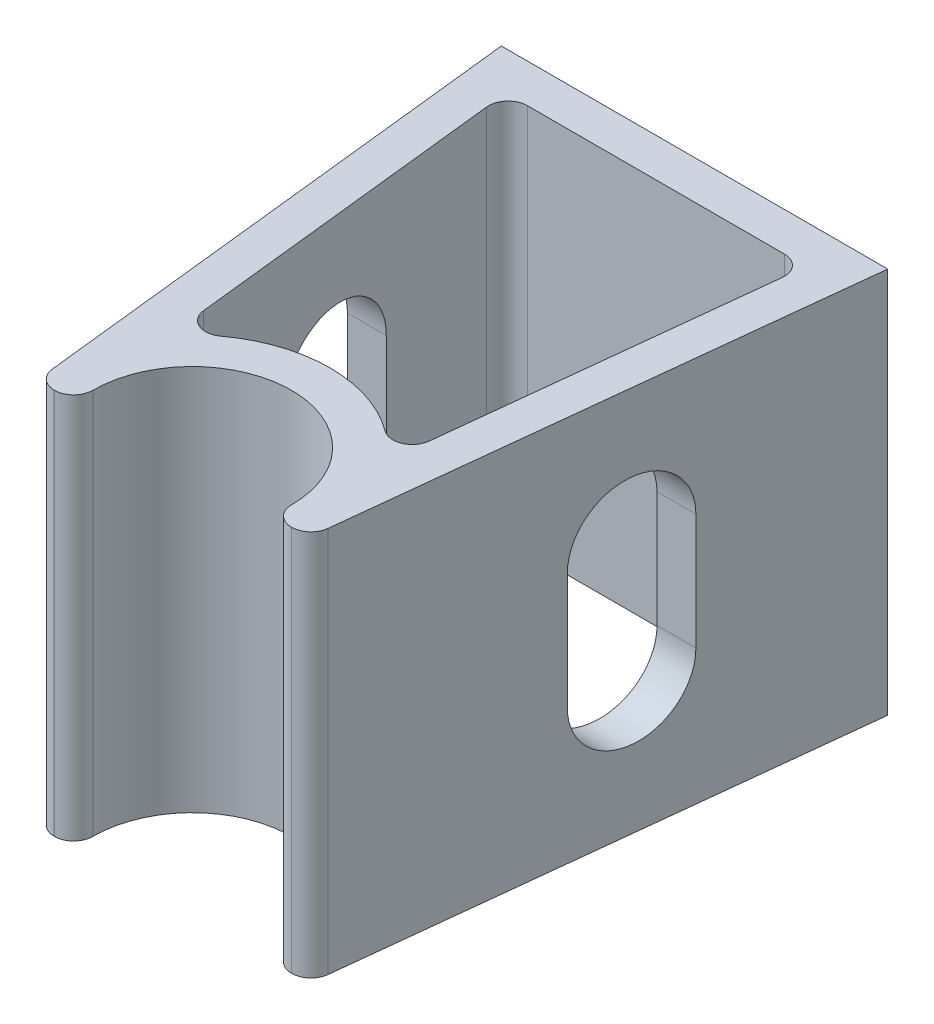
SolidWorks part; units mm, degrees
material "ABS"
ref_plane "Front Plane" through (0, 0, 0) normal (0, 0, 1) x (1, 0, 0)
ref_plane "Top Plane" through (0, 0, 0) normal (0, 1, 0) x (1, 0, 0)
ref_plane "Right Plane" through (0, 0, 0) normal (1, 0, 0) x (0, 0, -1)
sketch "Sketch1" plane through (0, 0, 0) normal (0, 1, 0) x (1, 0, 0)
  line L0 (-12.6, -2.5) -> (-17.6, -2.5)
  line L1 (-17.6, -2.5) -> (-25, 65)
  line L2 (-25, 65) -> (25, 65)
  line L3 (25, 65) -> (17.6, -2.5)
  line L4 (17.6, -2.5) -> (12.6, -2.5)
  arc A0 (12.6, -2.5) -> (-12.6, -2.5) centre (0, 0) ccw
  point P4 (0, 12.8456)
  dimension "D1" = 25.2
  dimension "D2" = 5
  dimension "D3" = 65
  dimension "D4" = 50
  dimension "D5" = 2.5
extrude "Boss-Extrude1" add sketch "Sketch1" along normal blind 50
sketch "Sketch2" plane through (0, 50, 0) normal (0, 1, 0) x (1, 0, 0)
  line L10 (14.0503, 11.0025) -> (19.4219, 60)
  line L11 (19.4219, 60) -> (-19.4219, 60)
  line L12 (-19.4219, 60) -> (-14.0503, 11.0025)
  line L13 (14.0503, 11.0025) -> (19.4219, 60)
  line L14 (19.4219, 60) -> (-19.4219, 60)
  line L15 (-19.4219, 60) -> (-14.0503, 11.0025)
  arc A2 (14.0503, 11.0025) -> (-14.0503, 11.0025) centre (0, 0) ccw
  arc A3 (14.0503, 11.0025) -> (-14.0503, 11.0025) centre (0, 0) ccw
  dimension "D1" = 5
extrude "Cut-Extrude1" cut sketch "Sketch2" against normal through all both and the other way through all
fillet "Fillet2" radius 2.5 8 edges at (-19.4219, 25, -60) (19.4219, 25, -60) (14.0503, 25, -11.0025) (-14.0503, 25, -11.0025) (17.6, 25, 2.5) (12.6, 25, 2.5) (-17.6, 25, 2.5) (-12.6, 25, 2.5)
sketch "Sketch3" plane through (0, 0, 0) normal (1, 0, 0) x (0, 0, -1)
  line L0 (35.1276, 0) -> (35.1276, 50) construction
  line L1 (-0.2724, 0) -> (65, 0) construction
  line L2 (-0.2724, 50) -> (65, 50) construction
  line L3 (35.1276, 32.5) -> (35.1276, 17.5) construction
  line L4 (42.6276, 32.5) -> (42.6276, 17.5)
  line L5 (27.6276, 32.5) -> (27.6276, 17.5)
  arc A1 (42.6276, 32.5) -> (27.6276, 32.5) centre (35.1276, 32.5) ccw
  arc A2 (27.6276, 17.5) -> (42.6276, 17.5) centre (35.1276, 17.5) ccw
  point P10 (35.1276, 25)
  dimension "D1" = 35.4
  dimension "D2" = 15
  dimension "D3" = 15
extrude "Cut-Extrude2" cut sketch "Sketch3" against normal through all both and the other way through all
sketch "Sketch4" plane through (0, 0, -65) normal (0, 0, -1) x (-1, 0, 0)
  text T0 "main_branch"
extrude "Boss-Extrude2" add sketch "Sketch4" along normal blind 1
